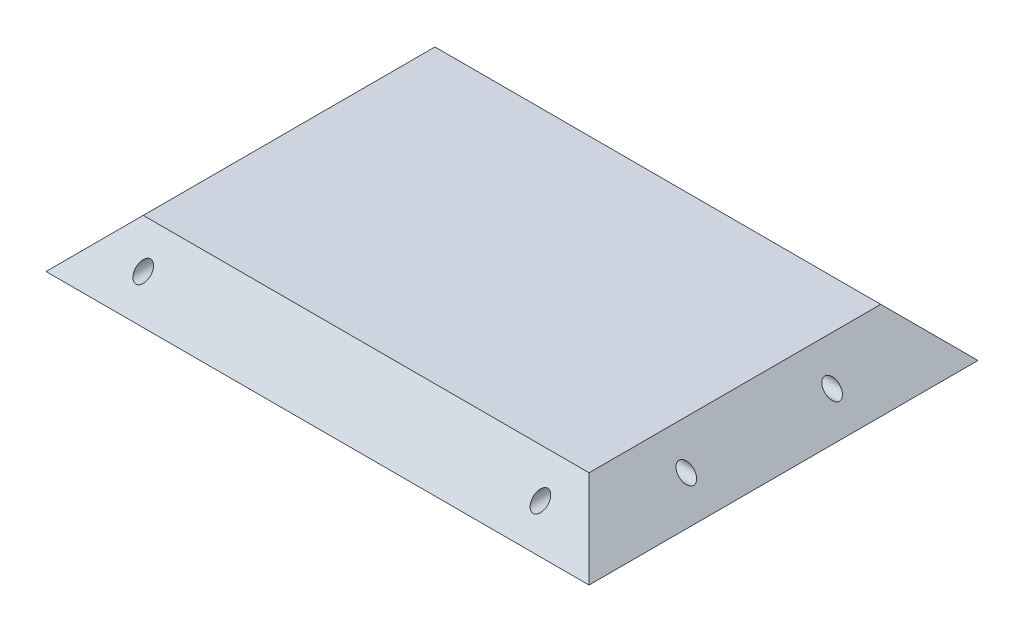
SolidWorks part; units mm, degrees
ref_plane "Спереди" through (0, 0, 0) normal (0, 0, 1) x (1, 0, 0)
ref_plane "Сверху" through (0, 0, 0) normal (0, 1, 0) x (1, 0, 0)
ref_plane "Справа" through (0, 0, 0) normal (1, 0, 0) x (0, 0, -1)
sketch "Эскиз1" plane through (0, 0, 0) normal (0, 1, 0) x (1, 0, 0)
  line L1 (-55.85, -40) -> (55.85, -40)
  line L2 (-55.85, -40) -> (-55.85, 40)
  line L3 (-55.85, 40) -> (55.85, 40)
  line L4 (55.85, -40) -> (55.85, 40)
  line L5 (-55.85, -40) -> (55.85, 40) construction
  line L6 (-55.85, 40) -> (55.85, -40) construction
  point P0 (0, 0)
  dimension "D1" = 111.7
  dimension "D2" = 80
ref_plane "Плоскость1" through (0, 10, 0) normal (0, 1, 0) x (1, 0, 0)
sketch "Эскиз2" plane through (0, 10, 0) normal (0, 1, 0) x (1, 0, 0)
  line L4 (-55.85, -40) -> (55.85, -40) construction
  line L5 (55.85, -40) -> (55.85, 40) construction
  line L6 (-55.85, 40) -> (55.85, 40) construction
  line L7 (-55.85, -40) -> (-55.85, 40) construction
  line L8 (45.85, 30) -> (-45.85, 30)
  line L9 (45.85, -30) -> (45.85, 30)
  line L10 (-45.85, 30) -> (-45.85, -30)
  line L11 (-45.85, -30) -> (45.85, -30)
  line L12 (45.85, 30) -> (-45.85, 30)
  line L13 (45.85, -30) -> (45.85, 30)
  line L14 (-45.85, 30) -> (-45.85, -30)
  line L15 (-45.85, -30) -> (45.85, -30)
  line L16 (-55.85, -40) -> (55.85, -40) construction
  line L17 (55.85, -40) -> (55.85, 40) construction
  line L18 (-55.85, 40) -> (55.85, 40) construction
  line L19 (-55.85, -40) -> (-55.85, 40) construction
  line L20 (-45.85, -30) -> (-45.85, -40) construction
  line L21 (-45.85, -30) -> (-55.85, -30) construction
  line L22 (-45.85, 30) -> (-45.85, 40) construction
  line L23 (-45.85, 30) -> (-55.85, 30) construction
  line L24 (45.85, -30) -> (45.85, -40) construction
  line L25 (45.85, -30) -> (55.85, -30) construction
  line L26 (45.85, 30) -> (45.85, 40) construction
  line L27 (45.85, 30) -> (55.85, 30) construction
  dimension "D1" = 10
loft "По сечениям1" add profiles "Эскиз1", "Эскиз2"
ref_plane "Плоскость2" through (0, 0, 40) normal (0, 0, 1) x (1, 0, 0)
sketch "Эскиз3" plane through (0, 0, 40) normal (0, 0, 1) x (1, 0, 0)
  line L0 (-55.85, 0) -> (-55.85, 10) construction
  line L1 (55.85, 0) -> (55.85, 10) construction
  line L2 (-55.85, 10) -> (55.85, 10) construction
  line L3 (45.85, 0) -> (45.85, 10) construction
  line L4 (-55.85, 0) -> (55.85, 0) construction
  line L5 (35.85, 10) -> (35.85, 5) construction
  line L6 (35.85, 5) -> (40.85, 5) construction
  line L7 (40.85, 5) -> (45.85, 5) construction
  line L8 (-55.85, 10) -> (55.85, 10) construction
  line L9 (0, 10) -> (0, 0) construction
  circle A0 centre (40.85, 5) radius 1.5
  circle A1 centre (-40.85, 5) radius 1.5
  dimension "D1" = 3
  dimension "D2" = 10
ref_plane "Плоскость3" through (0, 0, -40) normal (0, 0, -1) x (-1, 0, 0)
extrude "Вырез-Вытянуть1" cut sketch "Эскиз3" against normal blind 20 contours A0 | A1
mirror "Зеркальное отражение1" about plane through (0, 0, 0) normal (0, 0, 1) of "Вырез-Вытянуть1"
ref_plane "Плоскость4" through (55.85, 0, 0) normal (1, 0, 0) x (0, 0, -1)
sketch "Эскиз4" plane through (55.85, 0, 0) normal (1, 0, 0) x (0, 0, -1)
  line L0 (-40, 10) -> (-40, 0) construction
  line L1 (-40, 10) -> (40, 10) construction
  line L2 (40, 10) -> (40, 0) construction
  line L3 (-40, 10) -> (40, 10) construction
  line L4 (-20, 0) -> (-20, 10) construction
  line L5 (-40, 0) -> (40, 0) construction
  line L6 (-10, 10) -> (-10, 0) construction
  line L7 (-20, 5) -> (-10, 5) construction
  line L8 (0, 10) -> (0, 0) construction
  circle A0 centre (-15, 5) radius 1.5
  circle A1 centre (15, 5) radius 1.5
  dimension "D3" = 3
  dimension "D1" = 20
  dimension "D2" = 10
extrude "Вырез-Вытянуть2" cut sketch "Эскиз4" against normal blind 20 contours A1 | A0
mirror "Зеркальное отражение2" about plane through (0, 0, 0) normal (1, 0, 0) of "Вырез-Вытянуть2"
